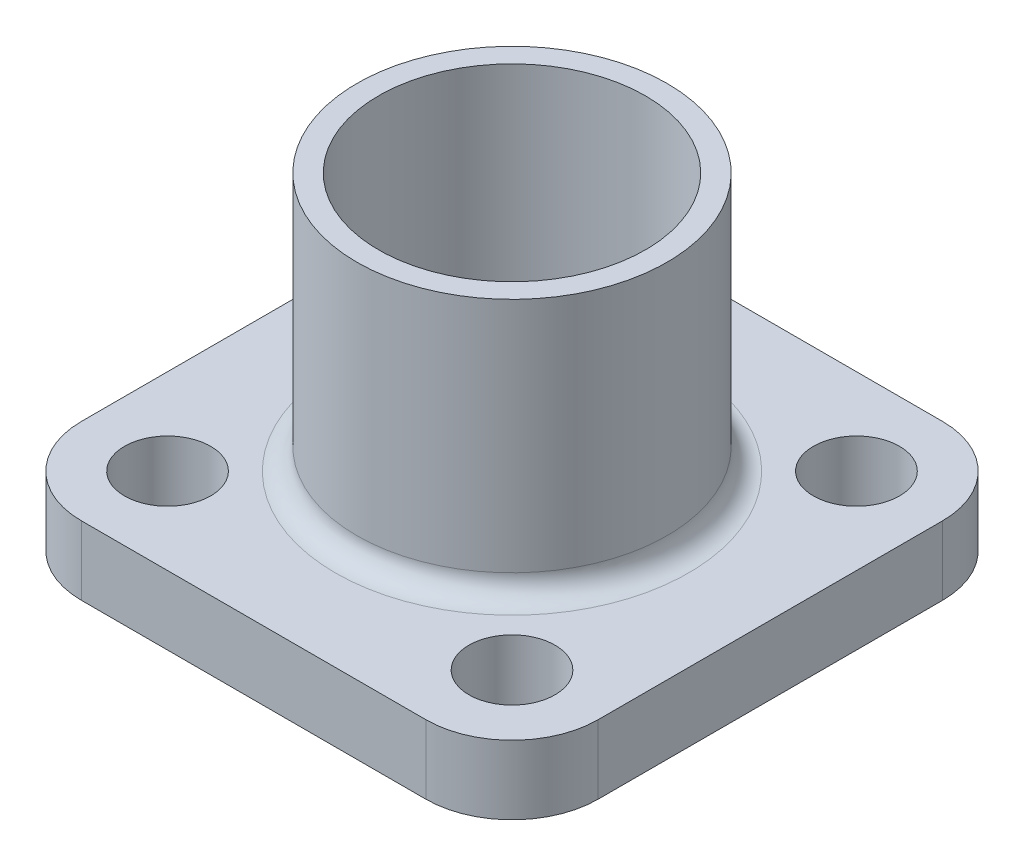
SolidWorks part; units mm, degrees
ref_plane "Front Plane" through (0, 0, 0) normal (0, 0, 1) x (1, 0, 0)
ref_plane "Top Plane" through (0, 0, 0) normal (0, 1, 0) x (1, 0, 0)
ref_plane "Right Plane" through (0, 0, 0) normal (1, 0, 0) x (0, 0, -1)
sketch "Sketch1" plane through (0, 0, 0) normal (0, 1, 0) x (1, 0, 0)
  line L1 (-6.35, -6.35) -> (6.35, -6.35) construction
  line L2 (-6.35, -6.35) -> (-6.35, 6.35) construction
  line L3 (-6.35, 6.35) -> (6.35, 6.35) construction
  line L4 (6.35, -6.35) -> (6.35, 6.35) construction
  line L5 (-6.35, -6.35) -> (6.35, 6.35) construction
  line L6 (-6.35, 6.35) -> (6.35, -6.35) construction
  line L7 (-9.525, -9.525) -> (9.525, -9.525)
  line L8 (-9.525, -9.525) -> (-9.525, 9.525)
  line L9 (-9.525, 9.525) -> (9.525, 9.525)
  line L10 (9.525, -9.525) -> (9.525, 9.525)
  line L11 (-9.525, -9.525) -> (9.525, 9.525) construction
  line L12 (-9.525, 9.525) -> (9.525, -9.525) construction
  circle A0 centre (-6.35, 6.35) radius 1.5875
  circle A1 centre (6.35, 6.35) radius 1.5875
  circle A2 centre (6.35, -6.35) radius 1.5875
  circle A3 centre (-6.35, -6.35) radius 1.5875
  circle A4 centre (0, 0) radius 3.9688
  point P0 (0, 0)
  point P6 (0, 0)
  dimension "D1" = 3.175
  dimension "D4" = 7.9375
  dimension "D2" = 19.05
  dimension "D3" = 12.7
extrude "Boss-Extrude1" add sketch "Sketch1" along normal blind 2.54
sketch "Sketch2" plane through (0, 2.54, 0) normal (0, 1, 0) x (1, 0, 0)
  circle A0 centre (0, 0) radius 4.9213
  circle A1 centre (0, 0) radius 5.715
  dimension "D1" = 9.8425
  dimension "D2" = 0.7937
extrude "Boss-Extrude2" add sketch "Sketch2" along normal blind 9.525
fillet "Fillet1" radius 0.7937 2 edges at (0, 2.54, 4.9213) (0, 2.54, -5.715)
fillet "Fillet2" radius 3.175 4 edges at (9.525, 1.27, -9.525) (-9.525, 1.27, -9.525) (9.525, 1.27, 9.525) (-9.525, 1.27, 9.525)
